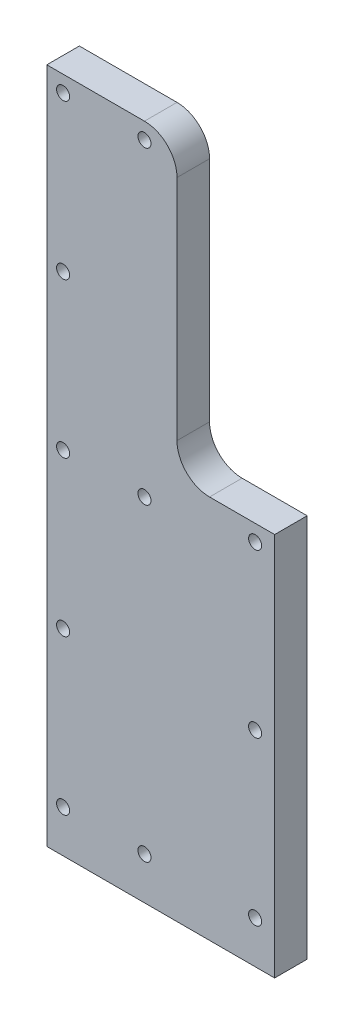
SolidWorks part; units mm, degrees
material "PLA"
ref_plane "Alzado" through (0, 0, 0) normal (0, 0, 1) x (1, 0, 0)
ref_plane "Planta" through (0, 0, 0) normal (0, 1, 0) x (1, 0, 0)
ref_plane "Vista lateral" through (0, 0, 0) normal (1, 0, 0) x (0, 0, -1)
sketch "Croquis1" plane through (0, 0, 0) normal (0, 0, 1) x (1, 0, 0)
  line L0 (0, 0) -> (0, 200)
  line L1 (0, 200) -> (30, 200)
  line L2 (40, 190) -> (40, 120)
  line L3 (50, 110) -> (70, 110)
  line L4 (70, 110) -> (70, 0)
  line L5 (70, 0) -> (0, 0)
  arc A0 (40, 120) -> (50, 110) centre (50, 120) ccw
  arc A1 (30, 200) -> (40, 190) centre (30, 190) cw
  point P11 (40, 110)
  point P14 (40, 200)
  dimension "D5" = 10
  dimension "D1" = 40
  dimension "D2" = 90
  dimension "D3" = 70
  dimension "D4" = 200
extrude "Saliente-Extruir1" add sketch "Croquis1" along normal blind 10
sketch "Croquis2" plane through (0, 0, 10) normal (0, 0, 1) x (1, 0, 0)
  line L0 (30, 200) -> (0, 200) construction
  line L1 (0, 200) -> (0, 0) construction
  line L2 (5, 200) -> (5, 0) construction
  line L3 (0, 0) -> (70, 0) construction
  line L4 (64, 110) -> (64, 0) construction
  line L5 (70, 110) -> (50, 110) construction
  line L6 (70, 0) -> (70, 110) construction
  line L7 (30, 200) -> (30, 0) construction
  circle A0 centre (5, 195) radius 2
  circle A1 centre (5, 147.5) radius 2
  circle A2 centre (5, 100) radius 2
  circle A3 centre (5, 52.5) radius 2
  circle A4 centre (5, 5) radius 2
  circle A5 centre (64, 105) radius 2
  circle A6 centre (64, 55) radius 2
  circle A7 centre (64, 5) radius 2
  circle A8 centre (30, 195) radius 2
  circle A9 centre (30, 100) radius 2
  circle A10 centre (30, 5) radius 2
  dimension "D1" = 4
  dimension "D7" = 4
  dimension "D8" = 5
  dimension "D12" = 4
  dimension "D14" = 5
  dimension "D2" = 5
  dimension "D3" = 5
  dimension "D5" = 5
  dimension "D6" = 6
  dimension "D10" = 5
  dimension "D11" = 5
  dimension "D4" = 5
  dimension "D9" = 3
  dimension "D13" = 3
extrude "Cortar-Extruir1" cut sketch "Croquis2" against normal through all
sketch "Croquis3" plane through (0, 0, 10) normal (0, 0, 1) x (1, 0, 0)
  line L0 (0, 0) -> (70, 0)
  line L1 (70, 0) -> (70, -8)
  line L2 (70, -8) -> (0, -8)
  line L3 (0, -8) -> (0, 0)
  dimension "D1" = 8
extrude "Saliente-Extruir2" add sketch "Croquis3" against normal blind 10
